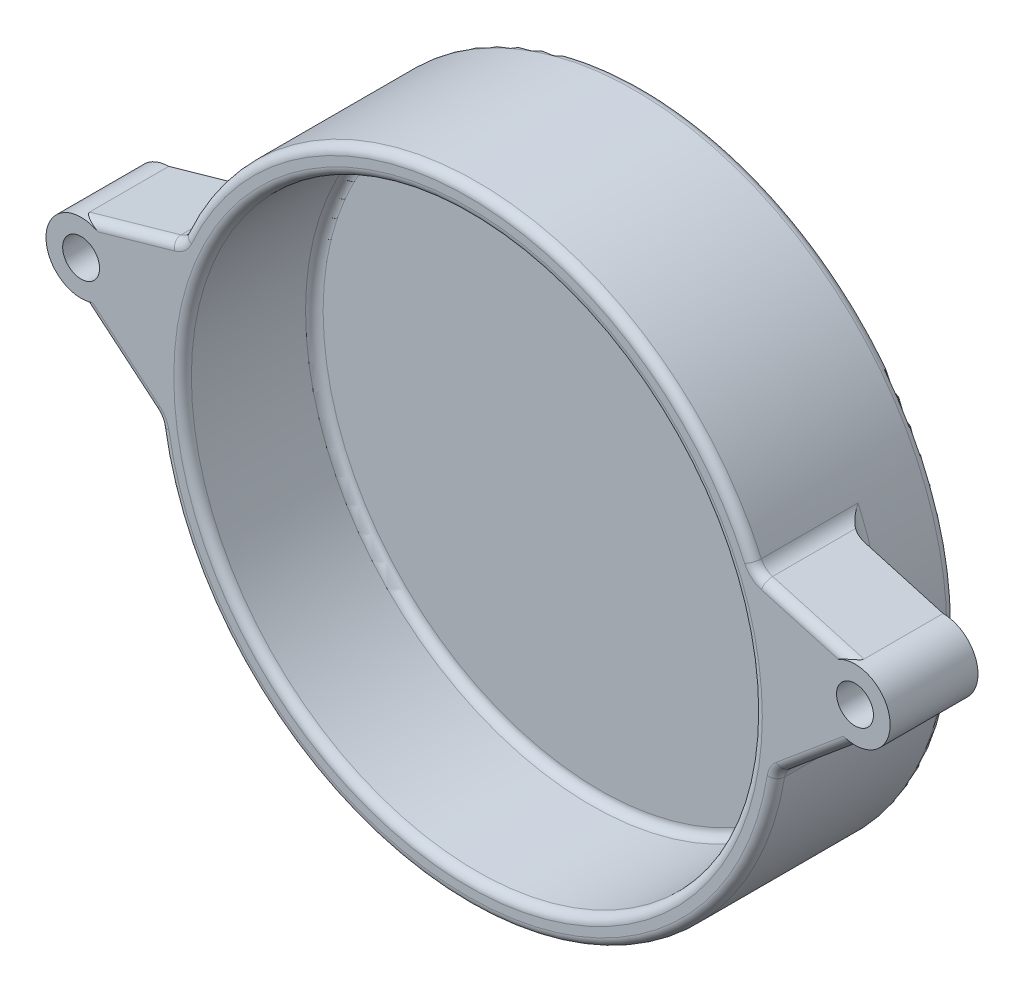
SolidWorks part; units mm, degrees
ref_plane "Front Plane" through (0, 0, 0) normal (0, 0, 1) x (1, 0, 0)
ref_plane "Top Plane" through (0, 0, 0) normal (0, 1, 0) x (1, 0, 0)
ref_plane "Right Plane" through (0, 0, 0) normal (1, 0, 0) x (0, 0, -1)
sketch "Sketch1" plane through (0, 0, 0) normal (0, 0, 1) x (1, 0, 0)
  circle A0 centre (0, 0) radius 32.5
  circle A1 centre (0, 0) radius 35.5
  dimension "D1" = 65
  dimension "D2" = 71
extrude "Boss-Extrude1" add sketch "Sketch1" along normal blind 20
sketch "Sketch2" plane through (0, 0, 0) normal (0, 0, -1) x (-1, 0, 0)
  circle A1 centre (0, 0) radius 35.5
  circle A2 centre (0, 0) radius 35.5
  dimension "D1" = 0
extrude "Boss-Extrude2" add sketch "Sketch2" against normal blind 5
sketch "Sketch3" plane through (0, 0, 0) normal (0, 0, -1) x (-1, 0, 0)
  line L0 (-42.5112, 13.033) -> (-32.3595, 14.5983)
  line L1 (-42.4509, 5.0333) -> (-35.4574, 1.7385)
  line L2 (0, 0) -> (0, 27.9534) construction
  line L3 (42.4509, 5.0333) -> (35.4574, 1.7385)
  line L4 (42.5112, 13.033) -> (32.3595, 14.5983)
  circle A1 centre (-42.481, 9.0331) radius 2
  arc A5 (42.5112, 13.033) -> (42.4509, 5.0333) centre (42.481, 9.0331) cw
  arc A7 (-42.5112, 13.033) -> (-42.4509, 5.0333) centre (-42.481, 9.0331) ccw
  circle A8 centre (0, 0) radius 35.5 construction
  arc A9 (-32.3595, 14.5983) -> (-35.4574, 1.7385) centre (0, 0) ccw
  circle A10 centre (42.481, 9.0331) radius 2
  arc A11 (35.4574, 1.7385) -> (32.3595, 14.5983) centre (0, 0) ccw
extrude "Boss-Extrude3" [suppressed] add sketch "Sketch3" against normal blind 10
sketch "Sketch5" plane through (0, 0, 20) normal (0, 0, 1) x (1, 0, 0)
  line L4 (-44.0198, 2.4626) -> (-35.1524, -4.9557)
  line L5 (-32.7617, 13.6719) -> (-44.0802, 10.4624)
  line L8 (44.0802, 10.4624) -> (32.7617, 13.6719)
  line L9 (35.1524, -4.9557) -> (44.0198, 2.4626)
  arc A4 (-44.0802, 10.4624) -> (-44.0198, 2.4626) centre (-44.05, 6.4625) ccw
  arc A5 (-32.7617, 13.6719) -> (-35.1524, -4.9557) centre (0, 0) ccw
  arc A8 (44.0198, 2.4626) -> (44.0802, 10.4624) centre (44.05, 6.4625) ccw
  arc A9 (35.1524, -4.9557) -> (32.7617, 13.6719) centre (0, 0) ccw
extrude "Boss-Extrude5" add sketch "Sketch5" against normal blind 10
sketch "Sketch6" plane through (0, 0, 10) normal (0, 0, -1) x (-1, 0, 0)
  circle A0 centre (-44.05, 6.4625) radius 2.1
  circle A1 centre (44.05, 6.4625) radius 2.1
  dimension "D1" = 4.2
  dimension "D2" = 4.2
extrude "Cut-Extrude1" cut sketch "Sketch6" against normal blind 10
fillet "Fillet1" radius 2 6 edges at (-35.1524, -4.9557, 15) (-35.2112, 4.5191, 10) (-32.7617, 13.6719, 15) (32.7617, 13.6719, 15) (35.1524, -4.9557, 15) (35.2112, 4.5191, 10)
fillet "Fillet2" radius 1 13 edges at (38.8774, 11.9377, 20) (32.9121, 13.8242, 20) (-38.8774, 11.9377, 20) (-32.9121, 13.8242, 20) (-39.8764, -1.0037, 20) (-35.2781, -5.0147, 20) (39.8764, -1.0037, 20) (35.2781, -5.0147, 20) (32.5, 0, 20) (0, 35.5, 20) (0, -35.5, 20) (35.5, 0, 0) (-32.5, 0, 5)
